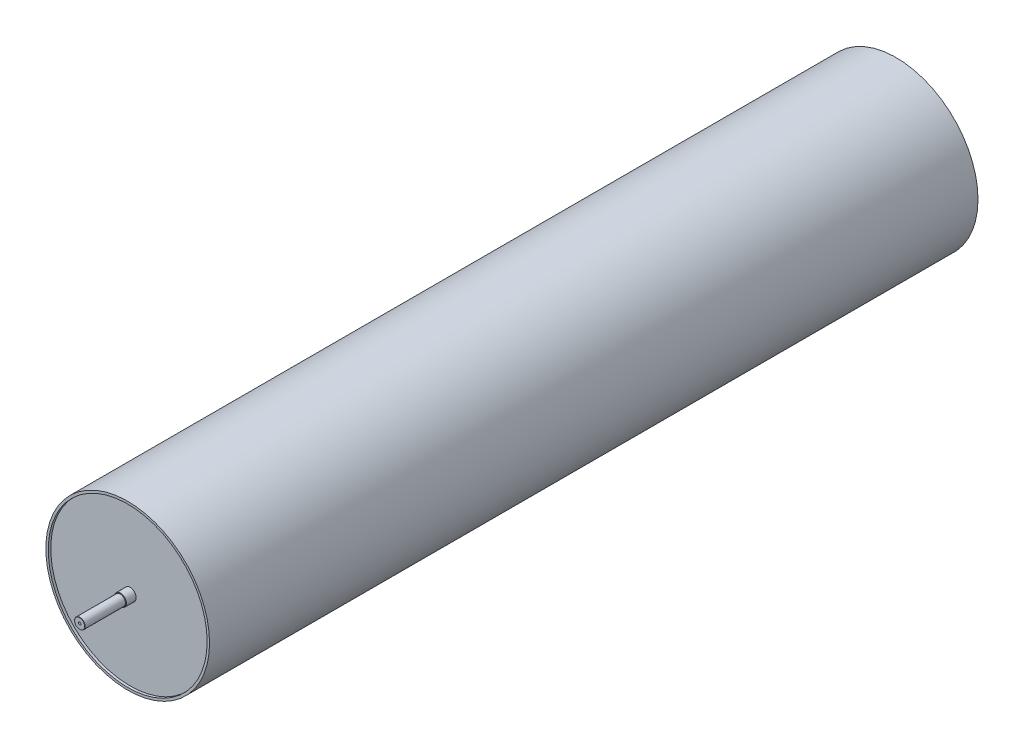
SolidWorks part; units mm, degrees
ref_plane "Front Plane" through (0, 0, 0) normal (0, 0, 1) x (1, 0, 0)
ref_plane "Top Plane" through (0, 0, 0) normal (0, 1, 0) x (1, 0, 0)
ref_plane "Right Plane" through (0, 0, 0) normal (1, 0, 0) x (0, 0, -1)
sketch "Sketch1" plane through (0, 0, 0) normal (0, 0, 1) x (1, 0, 0)
  circle A0 centre (0, 0) radius 165 construction
  circle A1 centre (0, 0) radius 158.7
  circle A2 centre (0, 0) radius 163.5
  dimension "D1" = 330
  dimension "D2" = 6.3
  dimension "D3" = 1.5
extrude "Boss-Extrude1" add sketch "Sketch1" along normal mid plane 1535
sketch "Sketch2" plane through (0, 0, 767.5) normal (0, 0, 1) x (1, 0, 0)
  circle A0 centre (0, 0) radius 158.7 construction
  circle A1 centre (0, 0) radius 158.7
extrude "Boss-Extrude2" add sketch "Sketch2" along normal blind 5 from offset 10 offset against normal yes
sketch "Sketch5" plane through (0, 0, 0) normal (1, 0, 0) x (0, 0, -1)
  line L0 (-782.5, 12) -> (782.5, 12)
  line L1 (782.5, 12) -> (782.5, 10.5)
  line L2 (782.5, 10.5) -> (863.5, 10.5)
  line L3 (863.5, 10.5) -> (863.5, 0)
  line L8 (863.5, 0) -> (-863.5, 0)
  line L9 (-863.5, 0) -> (-863.5, 10.5)
  line L14 (-863.5, 10.5) -> (-782.5, 10.5)
  line L15 (-782.5, 10.5) -> (-782.5, 12)
  line L16 (863.5, 0) -> (874, 0) construction
  line L18 (767.5, -163.5) -> (767.5, 163.5) construction
  point P20 (0, 12)
  dimension "D3" = 21
  dimension "D5" = 15
  dimension "D6" = 81
  dimension "D7" = 24
revolve "Revolve1" add sketch "Sketch5" angle 360 about L16
chamfer "Chamfer1" distance 0.5 4 edges at (0, -12, 782.5) (0, -12, -782.5) (0, -10.5, -863.5) (0, -10.5, 863.5)
hole_wizard "M6 Tapped Hole1" positions "Sketch6" profile "Sketch7" tap size "M6" standard "ISO"
sketch "Sketch6" plane through (0, 0, 863.5) normal (0, 0, 1) x (1, 0, 0)
  point P0 (0, 0)
sketch "Sketch7" plane through (0, 0, 863.5) normal (1, 0, 0) x (0, -1, 0)
  line L0 (0, 0) -> (0, 16.5022)
  line L1 (0, 16.5022) -> (2.5, 15)
  line L2 (2.5, 15) -> (2.5, 0)
  line L5 (2.5, 0) -> (0, 0)
  line L10 (0, 16.5022) -> (-2.5, 15) construction
  line L11 (0, -6.35) -> (0, 107.95) construction
  dimension "Tap Drill Dia." = 5
  dimension "Tap Drill Depth" = 15
  dimension "Drill Angle" = 118
cosmetic thread "Hole Thread1" parameters "D1"=12, "D2"=6
mirror "Mirror3" about plane through (0, 0, 0) normal (0, 0, 1) of "M6 Tapped Hole1", "Boss-Extrude2"
